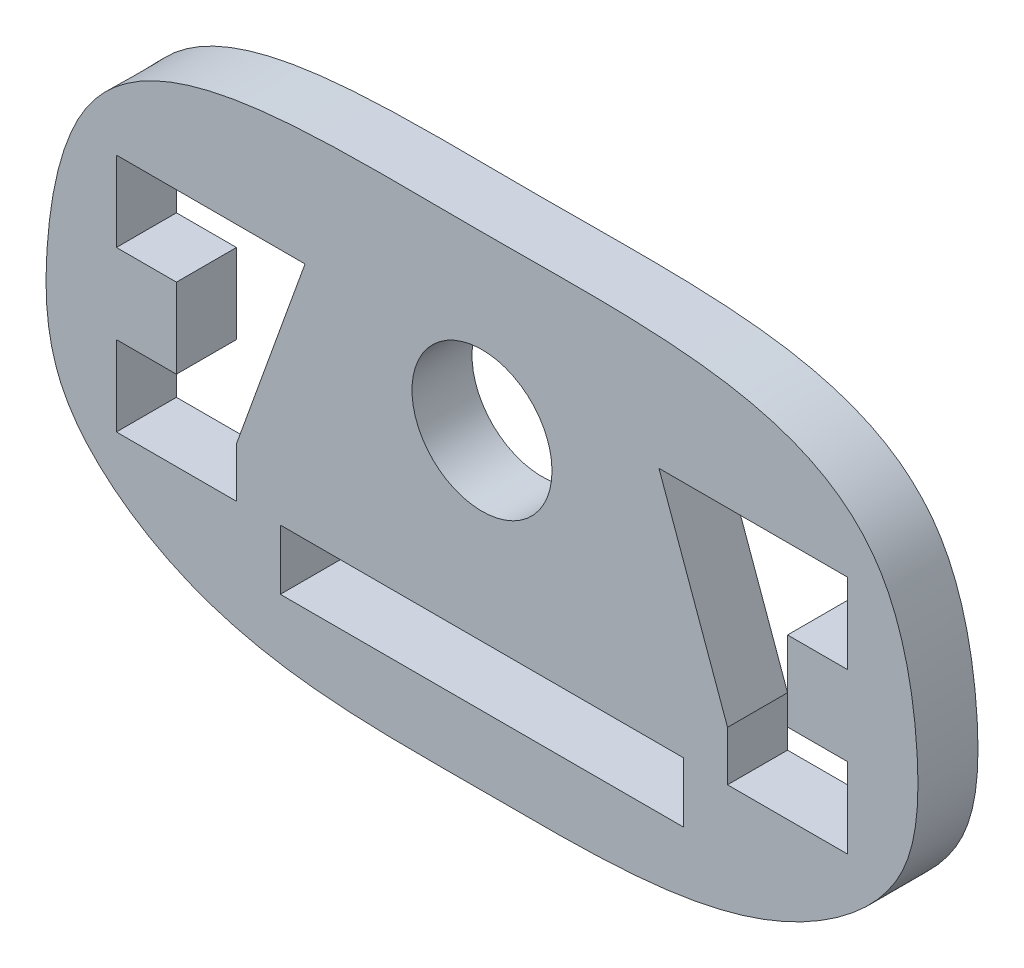
SolidWorks part; units mm, degrees
ref_plane "Front Plane" through (0, 0, 0) normal (0, 0, 1) x (1, 0, 0)
ref_plane "Top Plane" through (0, 0, 0) normal (0, 1, 0) x (1, 0, 0)
ref_plane "Right Plane" through (0, 0, 0) normal (1, 0, 0) x (0, 0, -1)
sketch "Sketch1" plane through (0, 0, 0) normal (0, 0, 1) x (1, 0, 0)
  line L0 (0, 0) -> (0, -9.133) construction
  line L1 (-10.08, -9.133) -> (10.08, -9.133)
  line L2 (-10.08, -9.133) -> (-10.08, -12.133)
  line L3 (-10.08, -12.133) -> (10.08, -12.133)
  line L4 (10.08, -12.133) -> (10.08, -9.133)
  line L5 (0, 0) -> (-8.846, 2.785) construction
  line L6 (-8.846, 2.785) -> (-18.273, 2.785)
  line L7 (-18.273, 2.785) -> (-18.273, -1.215)
  line L8 (-18.273, -1.215) -> (-15.273, -1.215)
  line L9 (-15.273, -1.215) -> (-15.273, -5.202)
  line L10 (-15.273, -5.202) -> (-18.273, -5.202)
  line L11 (-18.273, -5.202) -> (-18.273, -9.202)
  line L12 (-18.273, -9.202) -> (-12.273, -9.202)
  line L13 (-12.273, -9.202) -> (-12.273, -6.715)
  line L14 (-12.273, -6.715) -> (-8.846, 2.785)
  line L15 (12.273, -6.715) -> (8.846, 2.785)
  line L16 (12.273, -9.202) -> (12.273, -6.715)
  line L17 (18.273, -9.202) -> (12.273, -9.202)
  line L18 (18.273, -5.202) -> (18.273, -9.202)
  line L19 (15.273, -5.202) -> (18.273, -5.202)
  line L20 (15.273, -1.215) -> (15.273, -5.202)
  line L21 (18.273, -1.215) -> (15.273, -1.215)
  line L22 (18.273, 2.785) -> (18.273, -1.215)
  line L23 (8.846, 2.785) -> (18.273, 2.785)
  line L24 (0, 0) -> (0, 8.587) construction
  line L25 (0, 0) -> (0, -15.587) construction
  line L26 (0, 0) -> (-19.88, 3.92) construction
  line L27 (0, 0) -> (-21.747, -3.08) construction
  line L28 (0, 0) -> (-21, -8.587) construction
  line L29 (0, 0) -> (-16.707, -12.88) construction
  line L30 (0, 0) -> (16.707, -12.88) construction
  line L31 (0, 0) -> (21, -8.587) construction
  line L32 (0, 0) -> (21.747, -3.08) construction
  line L33 (0, 0) -> (19.88, 3.92) construction
  circle A0 centre (0, 0) radius 3.5
  spline S0 degree 3 poles (19.5336, 9.3745) (0, 8.0057) (-19.5336, 9.3745) (-21.9958, -2.5288) (-21.6736, -9.0453) (-13.85, -15.8842) (0, -15.3683) (13.85, -15.8842) (21.6736, -9.0453) (21.9958, -2.5288) (19.5336, 9.3745) (0, 8.0057) (-19.5336, 9.3745) knots -0.295476 -0.246049 -0.181616 0 0.181616 0.246049 0.295476 0.349473 0.5 0.650527 0.704524 0.753951 0.818384 1 1.181616 1.246049 1.295476 only from (0, 8.587) to (0, 8.587)
  point P7 (0, -9.133)
  dimension "D1" = 7
  dimension "D2" = 9.133
  dimension "D3" = 20.16
  dimension "D4" = 3
  dimension "D5" = 2.785
  dimension "D6" = 8.846
  dimension "D7" = 9.427
  dimension "D8" = 4
  dimension "D9" = 4
  dimension "D10" = 3.987
  dimension "D11" = 3
  dimension "D12" = 3
  dimension "D13" = 6
  dimension "D14" = 2.487
  dimension "D15" = 8.587
  dimension "D16" = 15.587
  dimension "D17" = 3.92
  dimension "D18" = 19.88
  dimension "D19" = 3.08
  dimension "D20" = 21.747
  dimension "D21" = 8.587
  dimension "D22" = 21
  dimension "D23" = 12.88
  dimension "D24" = 16.707
extrude "Boss-Extrude1" add sketch "Sketch1" against normal blind 3
